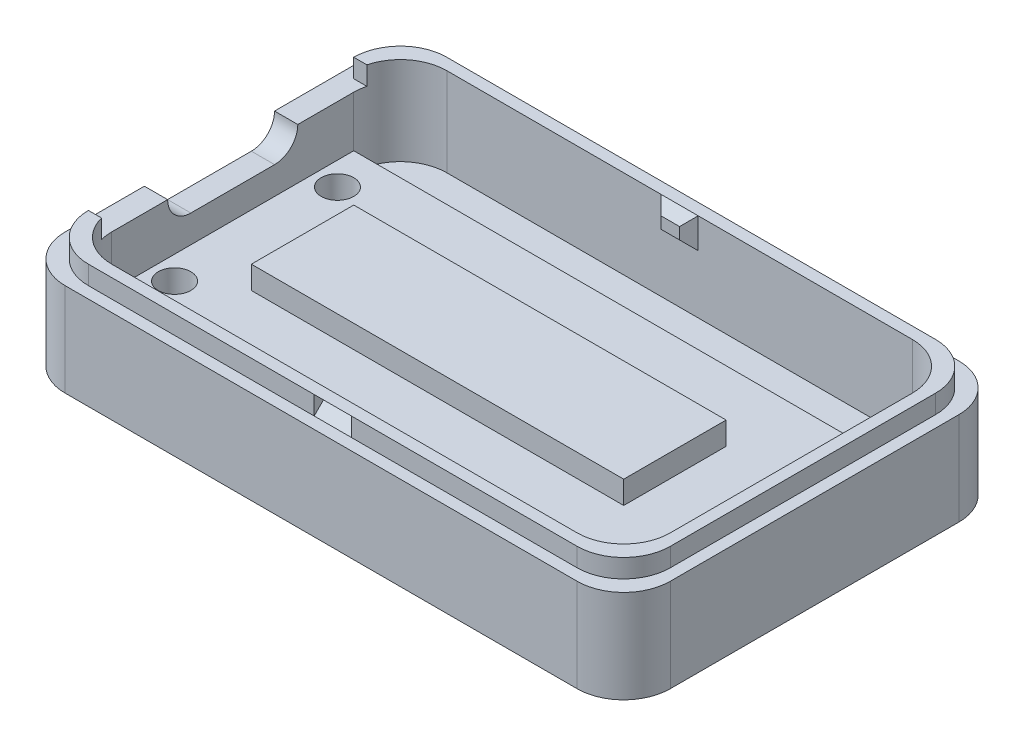
SolidWorks part; units mm, degrees
material "ABS"
ref_plane "Front Plane" through (0, 0, 0) normal (0, 0, 1) x (1, 0, 0)
ref_plane "Top Plane" through (0, 0, 0) normal (0, 1, 0) x (1, 0, 0)
ref_plane "Right Plane" through (0, 0, 0) normal (1, 0, 0) x (0, 0, -1)
sketch "Sketch2" plane through (0, 0, 0) normal (0, 1, 0) x (1, 0, 0)
  line L1 (0, 0) -> (55, 0)
  line L2 (0, 0) -> (0, 26)
  line L3 (0, 26) -> (55, 26)
  line L4 (55, 0) -> (55, 26)
extrude "Boss-Extrude3" add sketch "Sketch2" along normal blind 4.55
sketch "Sketch4" plane through (0, 0, 0) normal (0, 1, 0) x (1, 0, 0)
  line L1 (7.5, 18.5) -> (47.5, 18.5)
  line L2 (7.5, 18.5) -> (7.5, 7.5)
  line L3 (7.5, 7.5) -> (47.5, 7.5)
  line L4 (47.5, 18.5) -> (47.5, 7.5)
extrude "Boss-Extrude5" add sketch "Sketch4" along normal blind 7
sketch "Sketch5" plane through (0, 0, 0) normal (0, 1, 0) x (1, 0, 0)
  line L1 (5, 31) -> (55, 31)
  line L2 (0, 26) -> (0, 0)
  line L3 (5, -5) -> (55, -5)
  line L4 (60, 26) -> (60, 0)
  arc A0 (55, 31) -> (60, 26) centre (55, 26) cw
  arc A1 (60, 0) -> (55, -5) centre (55, 0) cw
  arc A2 (5, -5) -> (0, 0) centre (5, 0) cw
  arc A3 (0, 26) -> (5, 31) centre (5, 26) cw
  dimension "D1" = 5
extrude "Boss-Extrude6" add sketch "Sketch5" along normal blind 2.5
sketch "Sketch6" plane through (0, 0, 0) normal (0, 1, 0) x (1, 0, 0)
  line L1 (2.5, 33.5) -> (57.5, 33.5)
  line L2 (-2.5, 28.5) -> (-2.5, -2.5)
  line L3 (2.5, -7.5) -> (57.5, -7.5)
  line L4 (62.5, 28.5) -> (62.5, -2.5)
  line L5 (5, 31) -> (55, 31)
  line L6 (0, 26) -> (0, 0)
  line L7 (5, -5) -> (55, -5)
  line L8 (60, 26) -> (60, 0)
  arc A0 (57.5, 33.5) -> (62.5, 28.5) centre (57.5, 28.5) cw
  arc A1 (62.5, -2.5) -> (57.5, -7.5) centre (57.5, -2.5) cw
  arc A2 (2.5, -7.5) -> (-2.5, -2.5) centre (2.5, -2.5) cw
  arc A3 (-2.5, 28.5) -> (2.5, 33.5) centre (2.5, 28.5) cw
  arc A4 (60, 26) -> (55, 31) centre (55, 26) ccw
  arc A5 (60, 0) -> (55, -5) centre (55, 0) cw
  arc A6 (5, -5) -> (0, 0) centre (5, 0) cw
  arc A7 (0, 26) -> (5, 31) centre (5, 26) cw
  dimension "D1" = 5
  dimension "D2" = 5
extrude "Boss-Extrude7" add sketch "Sketch6" along normal blind 10
sketch "Sketch7" plane through (0, 0, 0) normal (1, 0, 0) x (0, 0, -1)
  line L0 (28.5, 10) -> (13, 10)
  line L1 (28.5, 10) -> (-2.5, 10) construction
  line L2 (13, 10) -> (6, 10)
  line L3 (26, 10) -> (0, 10) construction
  line L5 (17.5, 10) -> (8.5, 10) construction
  line L6 (17.5, 7.5096) -> (8.5, 7.5096)
  line L7 (17.5, 12.4904) -> (8.5, 12.4904)
  arc A0 (17.5, 7.5096) -> (17.5, 12.4904) centre (17.5, 10) ccw
  arc A1 (8.5, 12.4904) -> (8.5, 7.5096) centre (8.5, 10) ccw
  point P10 (13, 10)
ref_plane "Plane1" through (0, 10, 0) normal (0, 1, 0) x (1, 0, 0)
sketch "Sketch8" plane through (0, 10, 0) normal (0, 1, 0) x (1, 0, 0)
  line L1 (3.75, 32.25) -> (56.25, 32.25)
  line L3 (3.75, -6.25) -> (56.25, -6.25)
  line L4 (61.25, 27.25) -> (61.25, -1.25)
  line L5 (5, 31) -> (55, 31)
  line L7 (5, -5) -> (55, -5)
  line L8 (60, 26) -> (60, 0)
  line L20 (-1.25, -1.25) -> (0.1588, -1.25)
  line L21 (-1.25, 27.25) -> (0.1588, 27.25)
  arc A0 (56.25, 32.25) -> (61.25, 27.25) centre (56.25, 27.25) cw
  arc A1 (61.25, -1.25) -> (56.25, -6.25) centre (56.25, -1.25) cw
  arc A2 (3.75, -6.25) -> (-1.25, -1.25) centre (3.75, -1.25) cw
  arc A3 (-1.25, 27.25) -> (3.75, 32.25) centre (3.75, 27.25) cw
  arc A4 (55, 31) -> (60, 26) centre (55, 26) cw
  arc A5 (60, 0) -> (55, -5) centre (55, 0) cw
  arc A6 (5, -5) -> (0, 0) centre (5, 0) cw
  arc A7 (0.1588, 27.25) -> (5, 31) centre (5, 26) cw
  dimension "D1" = 5
  dimension "D2" = 5
extrude "Boss-Extrude9" add sketch "Sketch8" along normal blind 2
ref_plane "Plane2" through (30, 0, 0) normal (1, 0, 0) x (0, 0, -1)
sketch "Sketch9" plane through (30, 0, 0) normal (1, 0, 0) x (0, 0, -1)
  line L0 (-5, 12) -> (-4, 11)
  line L1 (-4, 11) -> (-4, 9.75)
  line L2 (-4, 9.75) -> (-5, 8.75)
  line L3 (-5, 12) -> (-5, 2.5) construction
  line L4 (-5, 8.75) -> (-5, 12)
  line L5 (31, 12) -> (30, 11)
  line L6 (30, 11) -> (30, 9.75)
  line L7 (30, 9.75) -> (31, 8.75)
  line L8 (31, 12) -> (31, 2.5) construction
  line L9 (31, 8.75) -> (31, 12)
  dimension "D1" = 1
extrude "Boss-Extrude10" add sketch "Sketch9" along normal blind 2 and the other way blind 2
sketch "Sketch10" plane through (30, 0, 0) normal (1, 0, 0) x (0, 0, -1)
  line L0 (-6.25, 12) -> (-5.25, 11)
  line L1 (-5.25, 11) -> (-6.25, 10)
  line L2 (-2.5, 10) -> (-7.5, 10) construction
  line L3 (-6.25, 12) -> (-6.25, 10) construction
  line L4 (-6.25, 10) -> (-6.25, 12)
  line L5 (32.25, 12) -> (31.25, 11)
  line L6 (31.25, 11) -> (32.25, 10)
  line L7 (32.25, 10) -> (32.25, 12)
extrude "Cut-Extrude2" cut sketch "Sketch10" against normal blind 2 and the other way blind 2
ref_plane "Plane3" through (0, 12, 0) normal (0, 1, 0) x (1, 0, 0)
sketch "Sketch11" plane through (0, 12, 0) normal (0, 1, 0) x (1, 0, 0)
  line L0 (32, 31) -> (32, 30)
  line L1 (32, 30) -> (31, 30)
  line L2 (28, 30) -> (32, 30) construction
  line L3 (31, 30) -> (32, 31)
  line L4 (28, 31) -> (28, 30)
  line L5 (28, 31) -> (28, 30) construction
  line L6 (28, 30) -> (29, 30)
  line L7 (29, 30) -> (28, 31)
  line L8 (28, -5) -> (28, -4)
  line L9 (28, -4) -> (29, -4)
  line L10 (28, -4) -> (32, -4) construction
  line L11 (29, -4) -> (28, -5)
  line L12 (32, -5) -> (32, -4)
  line L13 (32, -4) -> (32, -5) construction
  line L14 (32, -4) -> (31, -4)
  line L15 (31, -4) -> (32, -5)
extrude "Cut-Extrude3" cut sketch "Sketch11" against normal blind 4
sketch "Sketch12" plane through (30, 0, 0) normal (1, 0, 0) x (0, 0, -1)
  line L6 (28.5, 0) -> (-2.5, 0) construction
  line L7 (23.5, 0) -> (26, 0)
  line L8 (26, 0) -> (24.75, 1.25)
  line L9 (24.75, 1.25) -> (23.5, 0)
extrude "Cut-Extrude4" cut sketch "Sketch12" against normal blind 5 and the other way blind 5
extrude "Cut-Extrude6" cut sketch "Sketch7" against normal blind 10 contours L7 A1 L2 L0 A0 | L2 A1 L6 A0 L0
ref_plane "Plane4" through (0, 5, 0) normal (0, 1, 0) x (1, 0, 0)
sketch "Sketch14" plane through (0, 5, 0) normal (0, 1, 0) x (1, 0, 0)
  line L0 (0, 13) -> (0, 21.75)
  line L1 (0, 26) -> (0, 0) construction
  line L2 (0, 21.75) -> (2.5, 21.75)
  line L3 (0, 13) -> (0, 4.25)
  line L4 (0, 4.25) -> (2.5, 4.25)
  circle A0 centre (2.5, 21.75) radius 1.75
  circle A1 centre (2.5, 4.25) radius 1.75
extrude "Cut-Extrude7" cut sketch "Sketch14" against normal blind 4
